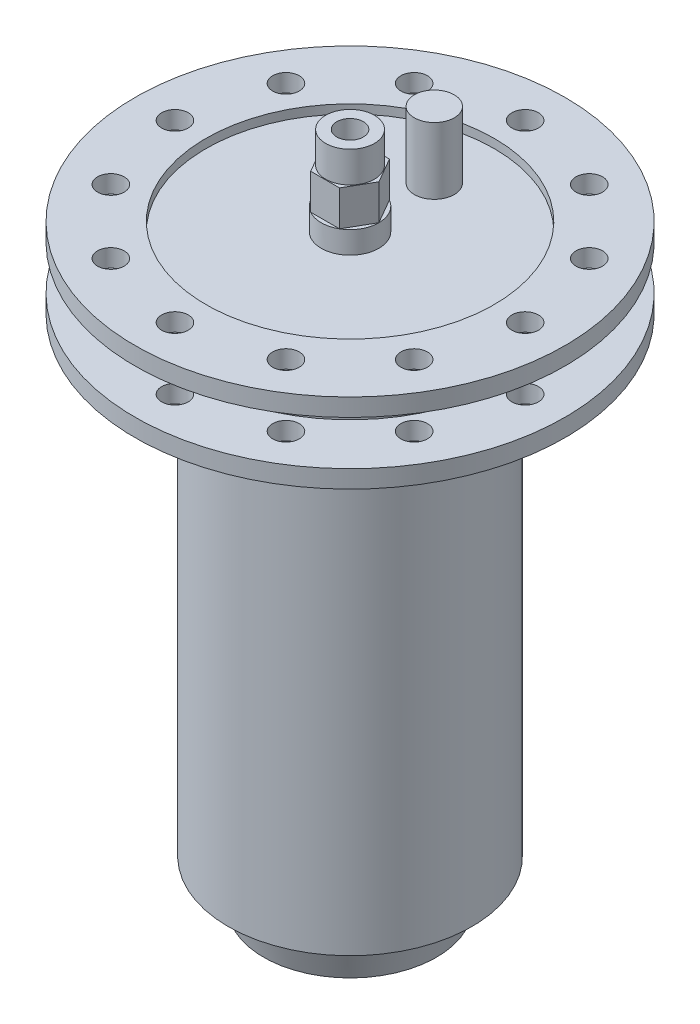
SolidWorks part; units mm, degrees
ref_plane "Спереди" through (0, 0, 0) normal (0, 0, 1) x (1, 0, 0)
ref_plane "Сверху" through (0, 0, 0) normal (0, 1, 0) x (1, 0, 0)
ref_plane "Справа" through (0, 0, 0) normal (1, 0, 0) x (0, 0, -1)
sketch "Эскиз1" plane through (0, 0, 0) normal (0, 0, 1) x (1, 0, 0)
  line L0 (0, 0) -> (0, 132) construction
  line L1 (10, 0) -> (19.5, 0)
  line L2 (19.5, 0) -> (22.5, 10)
  line L3 (22.5, 10) -> (27.5, 10)
  line L4 (27.5, 10) -> (27.5, 112)
  line L5 (32.5, 120) -> (32.5, 112)
  line L6 (32.5, 112) -> (27.5, 112)
  line L7 (32.5, 120) -> (35, 120)
  line L8 (35, 120) -> (35, 130)
  line L9 (35, 130) -> (32.5, 130)
  line L10 (32.5, 130) -> (32.5, 132)
  line L11 (32.5, 132) -> (0, 132)
  line L12 (10, 0) -> (5, 20)
  line L13 (5, 20) -> (0, 20)
  line L14 (0, 132) -> (0, 20)
  dimension "D1" = 132
  dimension "D2" = 55
  dimension "D3" = 45
  dimension "D4" = 39
  dimension "D5" = 10
  dimension "D6" = 20
  dimension "D7" = 65
  dimension "D8" = 70
  dimension "D9" = 65
  dimension "D10" = 10
  dimension "D11" = 2
  dimension "D12" = 20
  dimension "D13" = 20
  dimension "D14" = 5
revolve "Повернуть1" add sketch "Эскиз1" angle 360 about L0
sketch "Эскиз2" plane through (0, 0, 0) normal (1, 0, 0) x (0, 0, -1)
  line L0 (0, 0) -> (0, 132) construction
  line L1 (32.5, 132) -> (-32.5, 132) construction
  line L2 (32.5, 120) -> (48.5, 120)
  line L4 (48.5, 120) -> (48.5, 116)
  line L5 (48.5, 116) -> (32.5, 116)
  line L8 (32.5, 120) -> (32.5, 116)
  line L9 (32.5, 112) -> (32.5, 120) construction
  dimension "D1" = 4
  dimension "D2" = 97
revolve "Повернуть2" add sketch "Эскиз2" angle 360 about L0
ref_plane "Плоскость4" through (0, 125, 0) normal (0, 1, 0) x (1, 0, 0)
sketch "Эскиз3" plane through (0, 120, 0) normal (0, 1, 0) x (1, 0, 0)
  line L0 (0, 0) -> (48.5, 0) construction
  circle A0 centre (39.5, 0) radius 3
  circle A1 centre (0, 0) radius 48.5 construction
  dimension "D1" = 6
  dimension "D2" = 9
extrude "Вырез-Вытянуть1" cut sketch "Эскиз3" against normal blind 10
pattern_circular "Круговой массив1" count 12 over 360 about axis through (0, 0, 0) along (0, 1, 0) of "Вырез-Вытянуть1"
mirror "Зеркальное отражение2" about plane through (0, 125, 0) normal (0, 1, 0) of "Повернуть2", "Вырез-Вытянуть1", "Круговой массив1"
sketch "Эскиз4" plane through (0, 0, 0) normal (1, 0, 0) x (0, 0, -1)
  line L0 (0, 0) -> (0, 177.5372) construction
  line L2 (6.5, 132) -> (6.5, 145)
  line L3 (32.5, 132) -> (-32.5, 132) construction
  line L4 (6.5, 145) -> (5.5, 145)
  line L5 (5.5, 145) -> (5.5, 152)
  line L6 (5.5, 152) -> (3, 152)
  line L7 (3, 152) -> (3, 132)
  line L8 (6.5, 132) -> (3, 132)
  dimension "D1" = 13
  dimension "D2" = 13
  dimension "D3" = 11
  dimension "D4" = 20
  dimension "D5" = 6
revolve "Повернуть3" add sketch "Эскиз4" angle 360 about L0
sketch "Эскиз5" plane through (0, 145, 0) normal (0, 1, 0) x (1, 0, 0)
  line L1 (6.5, 0) -> (3.25, 5.6292)
  line L2 (3.25, 5.6292) -> (-3.25, 5.6292)
  line L3 (-3.25, 5.6292) -> (-6.5, 0)
  line L4 (-6.5, 0) -> (-3.25, -5.6292)
  line L5 (-3.25, -5.6292) -> (3.25, -5.6292)
  line L6 (3.25, -5.6292) -> (6.5, 0)
  circle A0 centre (0, 0) radius 5.6292 construction
  circle A1 centre (0, 0) radius 6.5
  circle M2 centre (0, 0) radius 6.5
extrude "Вырез-Вытянуть2" cut sketch "Эскиз5" against normal blind 8 contours L2 M2 | L1 M2 | L6 M2 | L5 M2 | L4 M2 | L3 M2
sketch "Эскиз7" plane through (0, 0, 0) normal (1, 0, 0) x (0, 0, -1)
  line L0 (19, 132) -> (19, 147) construction
  line L1 (32.5, 132) -> (-32.5, 132) construction
  line L2 (19, 147) -> (23.5, 147)
  line L3 (23.5, 147) -> (23.5, 132)
  line L4 (-6.5, 137) -> (-6.5, 132) construction
  line L5 (23.5, 132) -> (19, 132)
  line L6 (19, 132) -> (19, 147)
  dimension "D1" = 9
  dimension "D2" = 15
  dimension "D3" = 30
revolve "Повернуть5" add sketch "Эскиз7" angle 360 about L0
